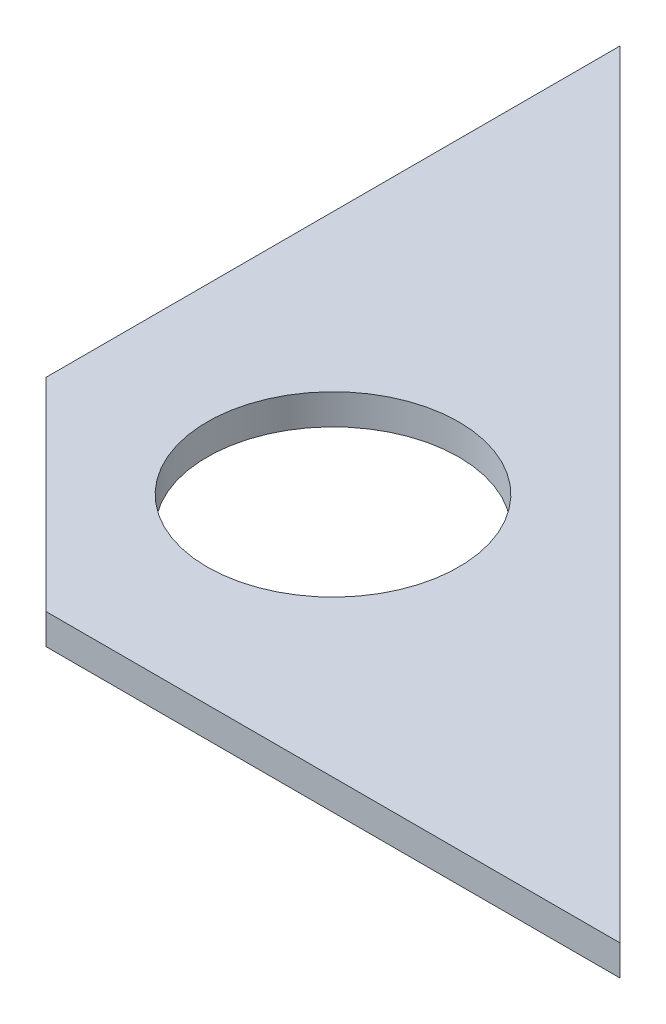
SolidWorks part; units mm, degrees
ref_plane "前基準面" through (0, 0, 0) normal (0, 0, 1) x (1, 0, 0)
ref_plane "上基準面" through (0, 0, 0) normal (0, 1, 0) x (1, 0, 0)
ref_plane "右基準面" through (0, 0, 0) normal (1, 0, 0) x (0, 0, -1)
sketch "草圖1" plane through (0, 0, 0) normal (0, 1, 0) x (1, 0, 0)
  line L0 (0, 76.5685) -> (0, 20)
  line L1 (0, 20) -> (20, 0)
  line L2 (20, 0) -> (76.5685, 0)
  line L3 (76.5685, 0) -> (0, 76.5685)
  line L4 (10, 10) -> (38.2843, 38.2843) construction
  circle A0 centre (24.1421, 24.1421) radius 12.4
  point P9 (0, 0)
  dimension "D2" = 24.8
  dimension "D1" = 20
  dimension "D3" = 20
  dimension "D4" = 40
extrude "填料-伸長1" add sketch "草圖1" along normal blind 3
